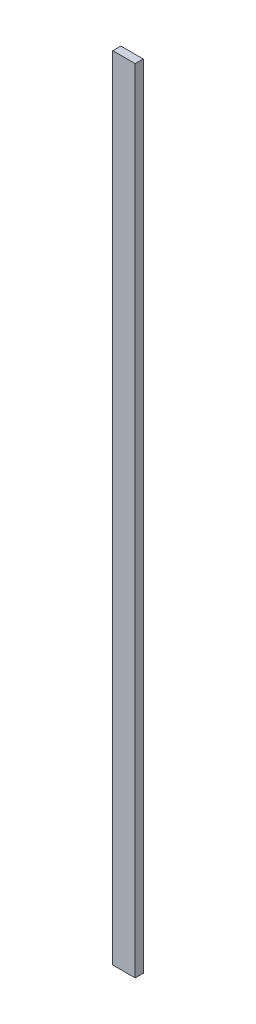
SolidWorks part; units mm, degrees
ref_plane "Front Plane" through (0, 0, 0) normal (0, 0, 1) x (1, 0, 0)
ref_plane "Top Plane" through (0, 0, 0) normal (0, 1, 0) x (1, 0, 0)
ref_plane "Right Plane" through (0, 0, 0) normal (1, 0, 0) x (0, 0, -1)
sketch "Sketch1" plane through (0, 0, 0) normal (0, 0, 1) x (1, 0, 0)
  line L1 (-25.4, -896.1438) -> (25.4, -896.1438)
  line L2 (-25.4, -896.1438) -> (-25.4, 896.1437)
  line L3 (-25.4, 896.1437) -> (25.4, 896.1437)
  line L4 (25.4, -896.1438) -> (25.4, 896.1437)
  line L5 (-25.4, -896.1438) -> (25.4, 896.1437) construction
  line L6 (-25.4, 896.1437) -> (25.4, -896.1438) construction
  point P0 (0, 0)
  dimension "D1" = 50.8
  dimension "D2" = 1792.2875
extrude "Boss-Extrude1" add sketch "Sketch1" along normal blind 18.2562
